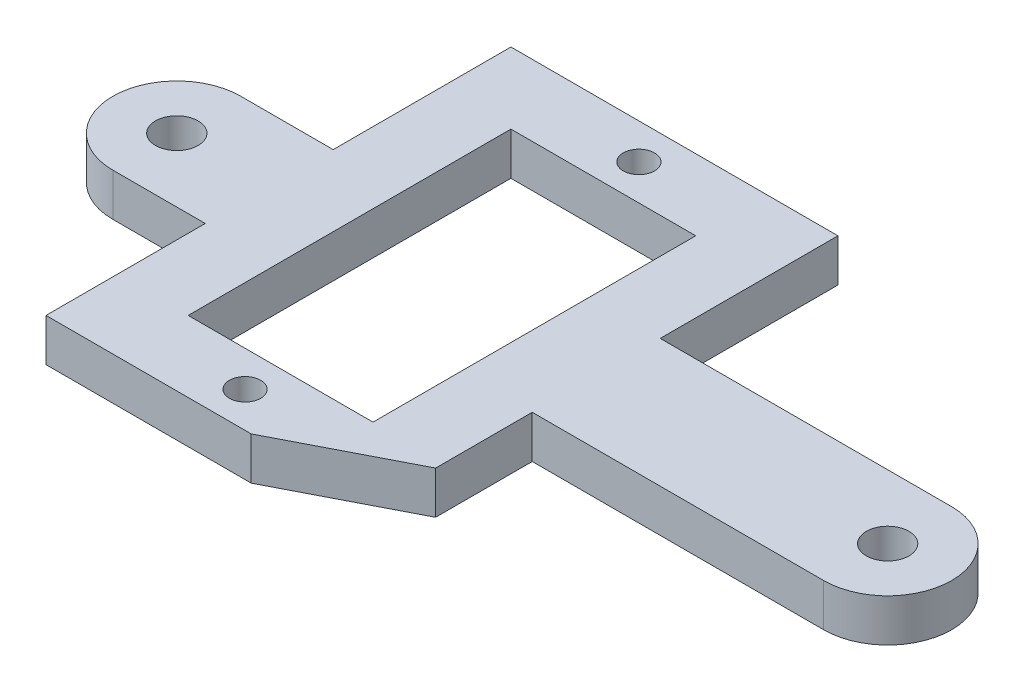
SolidWorks part; units mm, degrees
material "Thornel Mat VMA"
ref_plane "前视基准面" through (0, 0, 0) normal (0, 0, 1) x (1, 0, 0)
ref_plane "上视基准面" through (0, 0, 0) normal (0, 1, 0) x (1, 0, 0)
ref_plane "右视基准面" through (0, 0, 0) normal (1, 0, 0) x (0, 0, -1)
other "Configuration Table"
sketch "草图1" plane through (0, 0, 0) normal (0, 1, 0) x (1, 0, 0)
  line L0 (25, 0) -> (-25, 0) construction
  line L1 (-25, 4.5) -> (25, 4.5)
  line L2 (25, -4.5) -> (-25, -4.5)
  line L3 (-7, 14.5) -> (-7, -13.2) construction
  line L4 (2, 14.5) -> (-16, 14.5) construction
  line L5 (-0.5, -10.7) -> (-13.5, -10.7)
  line L10 (-0.5, -10.7) -> (-0.5, 12)
  line L11 (-0.5, 12) -> (-13.5, 12)
  line L12 (-13.5, -10.7) -> (-13.5, 12)
  line L13 (-0.5, -10.7) -> (-13.5, 12) construction
  line L18 (-0.5, 12) -> (-13.5, -10.7) construction
  line L19 (-16, 14.5) -> (-16, 4.5) construction
  line L20 (2, 14.5) -> (2, 4.5) construction
  line L21 (4.5, 17) -> (4.5, 0)
  line L22 (5.4003, -15.7) -> (8.6277, -15.7)
  line L24 (5.4003, -10.7) -> (6.9236, -10.7)
  line L27 (4.5, 17) -> (-18.5, 17)
  line L28 (-18.5, 17) -> (-18.5, 4.5)
  line L31 (-9.5427, 0.65) -> (-2.1136, 0.65) construction
  line L32 (4.5, -15.7) -> (4.5, 0)
  line L33 (4.5, -15.7) -> (-18.5, -15.7)
  line L34 (-18.5, -15.7) -> (-18.5, 4.5)
  line L35 (4.5, 17) -> (4.5, 4.5) construction
  circle A0 centre (-25, 0) radius 1.5
  circle A1 centre (25, 0) radius 1.5
  circle A2 centre (-25, 0) radius 4.5
  circle A3 centre (25, 0) radius 4.5
  circle A4 centre (-7, -13.2) radius 1.1
  circle A5 centre (-7, 14.5) radius 1.1
  circle A10 centre (-7, -13.2) radius 2.5
  circle A11 centre (-7, 14.5) radius 2.5
  point P3 (0, 0.65)
  point P4 (0, 0)
  point P15 (-7, 0.65)
  point P32 (-7, 14.5)
  dimension "D2" = 3
  dimension "D3" = 3
  dimension "D5" = 2.2
  dimension "D6" = 13.2
  dimension "D7" = 5
  dimension "D8" = 13
  dimension "D1" = 14.5
  dimension "D9" = 18
  dimension "D10" = 2.5
  dimension "D11" = 2.5
  dimension "D12" = 50
  dimension "D4" = 3
extrude "凸台-拉伸1" add sketch "草图1" along normal blind 3 contours A2 A0 | A2 L2 L34 L1 | L34 L2 L12 L1 | A10 L5 L12 L2 L34 L33 | A10 L33 L32 L2 L10 L5 | L2 L32 L21 L1 L10 | A11 L11 L10 L1 L21 L27 | A11 L27 L28 L1 L12 L11 | A3 L1 L21 L32 L2 | A3 A1 | A11 A5 | A10 A4
sketch "草图2" plane through (0, 3, 0) normal (0, 1, 0) x (1, 0, 0)
  line L0 (4.5, -11.296) -> (-4.065, -15.7)
  line L1 (4.5, -15.7) -> (4.5, -4.5) construction
  line L2 (4.5, -15.7) -> (-18.5, -15.7) construction
  line L12 (4.5, -15.7) -> (4.5, -4.5)
  line L13 (-18.5, 4.5) -> (-25, 4.5)
  line L14 (-25, -4.5) -> (-18.5, -4.5)
  line L15 (-18.5, -4.5) -> (-18.5, -15.7)
  line L16 (-18.5, -15.7) -> (4.5, -15.7)
  line L18 (4.5, -15.7) -> (4.5, -4.5)
  line L20 (4.5, -4.5) -> (25, -4.5)
  line L21 (4.5, 17) -> (-18.5, 17)
  line L22 (-18.5, 17) -> (-18.5, 4.5)
  line L23 (-18.5, 4.5) -> (-25, 4.5)
  line L24 (-25, -4.5) -> (-18.5, -4.5)
  line L25 (-18.5, -4.5) -> (-18.5, -15.7)
  line L26 (-18.5, -15.7) -> (4.5, -15.7)
  line L31 (4.5, 17) -> (-18.5, 17)
  line L32 (-18.5, 17) -> (-18.5, 4.5)
  line L34 (-18.5, -15.7) -> (4.5, -15.7)
  line L35 (4.5, -15.7) -> (4.5, -4.5)
  line L36 (4.5, -4.5) -> (25, -4.5)
  line L37 (25, 4.5) -> (4.5, 4.5)
  line L38 (4.5, 4.5) -> (4.5, 17)
  line L39 (4.5, 17) -> (-18.5, 17)
  line L40 (-25, -4.5) -> (-18.5, -4.5)
  line L41 (-25, -4.5) -> (-18.5, -4.5)
  line L42 (-18.5, -4.5) -> (-18.5, -15.7)
  line L43 (-18.5, -15.7) -> (4.5, -15.7)
  line L44 (4.5, -15.7) -> (4.5, -4.5)
  line L45 (4.5, -4.5) -> (25, -4.5)
  line L46 (25, 4.5) -> (4.5, 4.5)
  line L47 (4.5, 4.5) -> (4.5, 17)
  line L48 (4.5, 17) -> (-18.5, 17)
  line L53 (4.5, -4.5) -> (25, -4.5)
  line L54 (25, 4.5) -> (4.5, 4.5)
  line L55 (25, 4.5) -> (4.5, 4.5)
  line L56 (4.5, 4.5) -> (4.5, 17)
  line L57 (4.5, 4.5) -> (4.5, 17)
  line L58 (-18.5, -4.5) -> (-18.5, -15.7)
  line L59 (-18.5, 17) -> (-18.5, 4.5)
  line L60 (-18.5, 17) -> (-18.5, 4.5)
  line L61 (-18.5, 4.5) -> (-25, 4.5)
  line L62 (-18.5, 4.5) -> (-25, 4.5)
  arc A2 (-25, 4.5) -> (-25, -4.5) centre (-25, 0) ccw
  arc A3 (25, -4.5) -> (25, 4.5) centre (25, 0) ccw
  arc A4 (-25, 4.5) -> (-25, -4.5) centre (-25, 0) ccw
  arc A6 (25, -4.5) -> (25, 4.5) centre (25, 0) ccw
  arc A8 (-25, 4.5) -> (-25, -4.5) centre (-25, 0) ccw
  arc A10 (-25, 4.5) -> (-25, -4.5) centre (-25, 0) ccw
  arc A11 (25, -4.5) -> (25, 4.5) centre (25, 0) ccw
  arc A14 (25, -4.5) -> (25, 4.5) centre (25, 0) ccw
  line M21 (-18.5, -15.7) -> (4.5, -15.7)
  line M22 (4.5, -15.7) -> (4.5, -4.5)
  dimension "D1" = 0
  dimension "D2" = 0
extrude "切除-拉伸1" cut sketch "草图2" against normal through all contours L0 M22 M21
